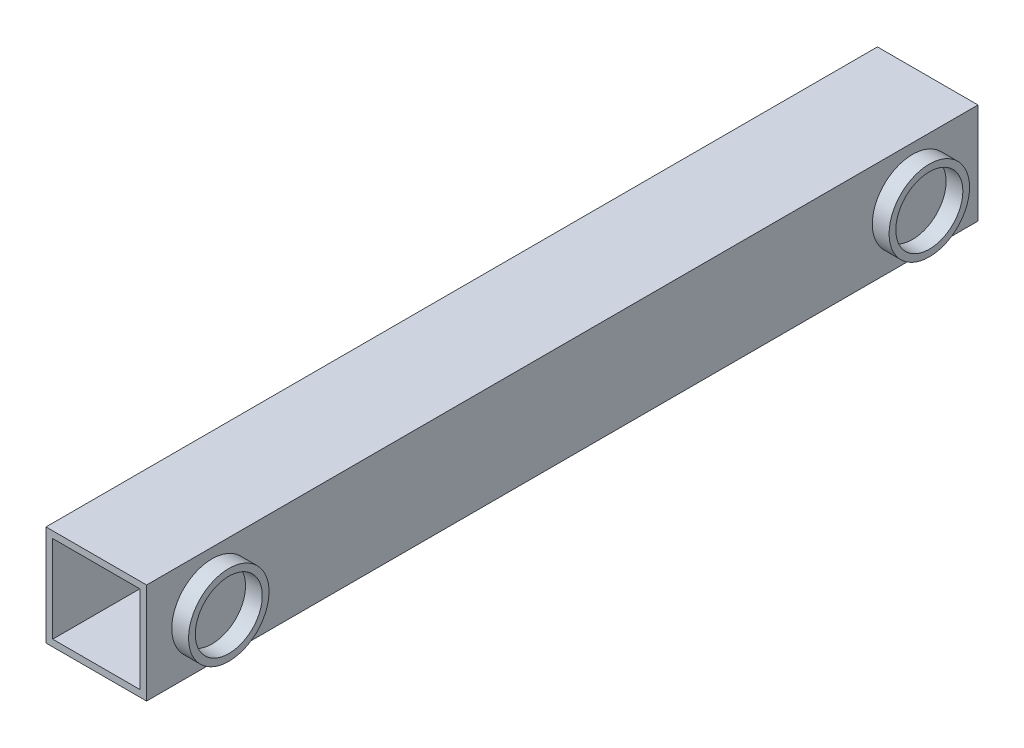
SolidWorks part; units mm, degrees
material "6063-T6"
ref_plane "Front Plane" through (0, 0, 0) normal (0, 0, 1) x (1, 0, 0)
ref_plane "Top Plane" through (0, 0, 0) normal (0, 1, 0) x (1, 0, 0)
ref_plane "Right Plane" through (0, 0, 0) normal (1, 0, 0) x (0, 0, -1)
sketch "Sketch1" plane through (0, 0, 0) normal (0, 0, 1) x (1, 0, 0)
  line L0 (-13, 13) -> (-13, -13)
  line L1 (-15, 15) -> (15, 15)
  line L2 (-15, 15) -> (-15, -15)
  line L3 (-15, -15) -> (15, -15)
  line L4 (15, 15) -> (15, -15)
  line L5 (-15, 15) -> (15, -15) construction
  line L6 (-15, -15) -> (15, 15) construction
  line L7 (-13, -13) -> (13, -13)
  line L8 (13, 13) -> (13, -13)
  line L9 (-13, 13) -> (13, 13)
  point P0 (0, 0)
  dimension "D1" = 30
  dimension "D2" = 30
  dimension "D3" = 2
extrude "Boss-Extrude1" add sketch "Sketch1" along normal blind 248
sketch "Sketch2" plane through (15, 0, 0) normal (1, 0, 0) x (0, 0, -1)
  line L0 (-124, 15) -> (-124, -15) construction
  line L1 (-248, 15) -> (0, 15) construction
  line L2 (-248, -15) -> (0, -15) construction
  circle A0 centre (-19.5223, 0) radius 12
  circle A1 centre (-19.5223, 0) radius 10
  circle A2 centre (-228.4777, 0) radius 12
  circle A3 centre (-228.4777, 0) radius 10
  dimension "D1" = 24
  dimension "D2" = 2
extrude "Boss-Extrude2" add sketch "Sketch2" along normal blind 5
